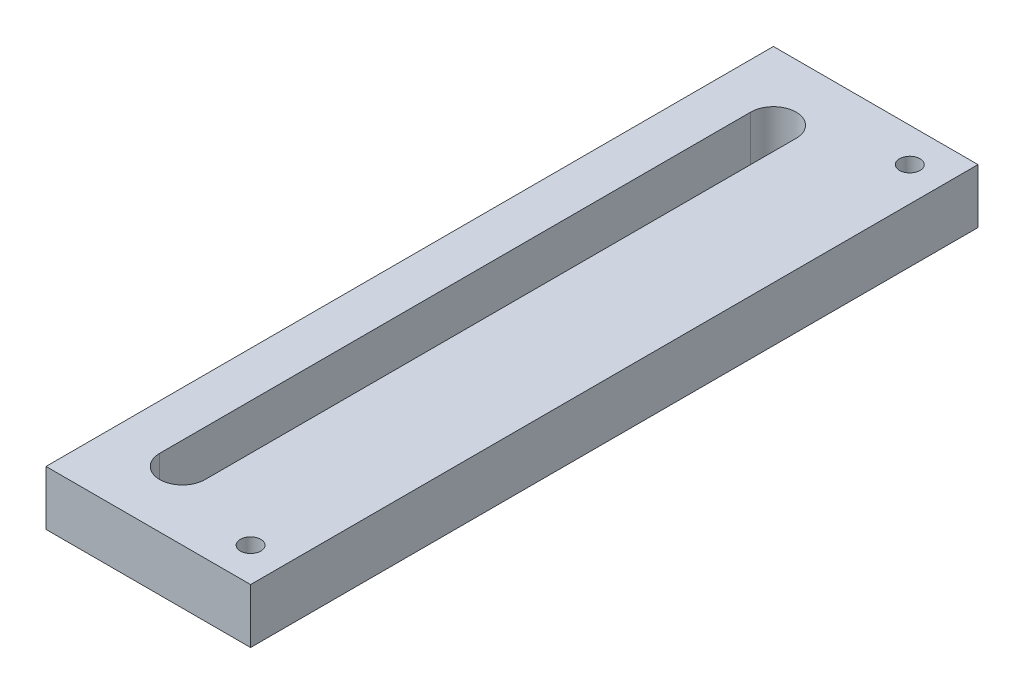
SolidWorks part; units mm, degrees
ref_plane "Front Plane" through (0, 0, 0) normal (0, 0, 1) x (1, 0, 0)
ref_plane "Top Plane" through (0, 0, 0) normal (0, 1, 0) x (1, 0, 0)
ref_plane "Right Plane" through (0, 0, 0) normal (1, 0, 0) x (0, 0, -1)
sketch "Sketch2" plane through (0, 0, 0) normal (0, 1, 0) x (1, 0, 0)
  line L1 (22.5, -80) -> (-22.5, -80)
  line L2 (22.5, -80) -> (22.5, 80)
  line L3 (22.5, 80) -> (-22.5, 80)
  line L4 (-22.5, -80) -> (-22.5, 80)
  line L5 (22.5, -80) -> (-22.5, 80) construction
  line L6 (22.5, 80) -> (-22.5, -80) construction
  point P0 (0, 0)
  dimension "D1" = 45
  dimension "D2" = 160
extrude "Boss-Extrude3" add sketch "Sketch2" along normal blind 12
sketch "Sketch3" plane through (0, 12, 0) normal (0, 1, 0) x (1, 0, 0)
  line L0 (22.5, 80) -> (22.5, 72.5)
  line L1 (22.5, -80) -> (22.5, 80) construction
  line L2 (22.5, 72.5) -> (15, 72.5)
  line L3 (22.5, -80) -> (22.5, -72.5)
  line L4 (22.5, -72.5) -> (15, -72.5)
  circle A0 centre (15, 72.5) radius 2.25
  circle A1 centre (15, -72.5) radius 2.25
  dimension "D3" = 4.5
  dimension "D6" = 4.5
  dimension "D1" = 7.5
  dimension "D2" = 7.5
  dimension "D4" = 7.5
  dimension "D5" = 7.5
extrude "Cut-Extrude3" cut sketch "Sketch3" against normal blind 5 contours A0 | A1
sketch "Sketch5" plane through (0, 7, 0) normal (0, 1, 0) x (1, 0, 0)
  line L0 (-22.5, -80) -> (22.5, -80) construction
  circle A0 centre (15, 72.5) radius 5
  dimension "D1" = 10
extrude "Cut-Extrude5" cut sketch "Sketch5" against normal blind 7
mirror "Mirror1" about plane through (0, 0, 0) normal (0, 0, 1) of "Cut-Extrude3", "Cut-Extrude5"
sketch "Sketch6" plane through (0, 12, 0) normal (0, 1, 0) x (1, 0, 0)
  line L0 (-51.0044, 0) -> (74.3126, 0) construction
  line L1 (-7.5, -65) -> (-7.5, 65) construction
  line L2 (-12.5, -65) -> (-12.5, 65)
  line L3 (-2.5, -65) -> (-2.5, 65)
  line L4 (-22.5, 80) -> (-22.5, -80) construction
  arc A0 (-12.5, -65) -> (-2.5, -65) centre (-7.5, -65) ccw
  arc A1 (-2.5, 65) -> (-12.5, 65) centre (-7.5, 65) ccw
  point P5 (-7.5, 0)
  dimension "D2" = 5
  dimension "D1" = 130
  dimension "D3" = 15
extrude "Cut-Extrude6" cut sketch "Sketch6" against normal through all
